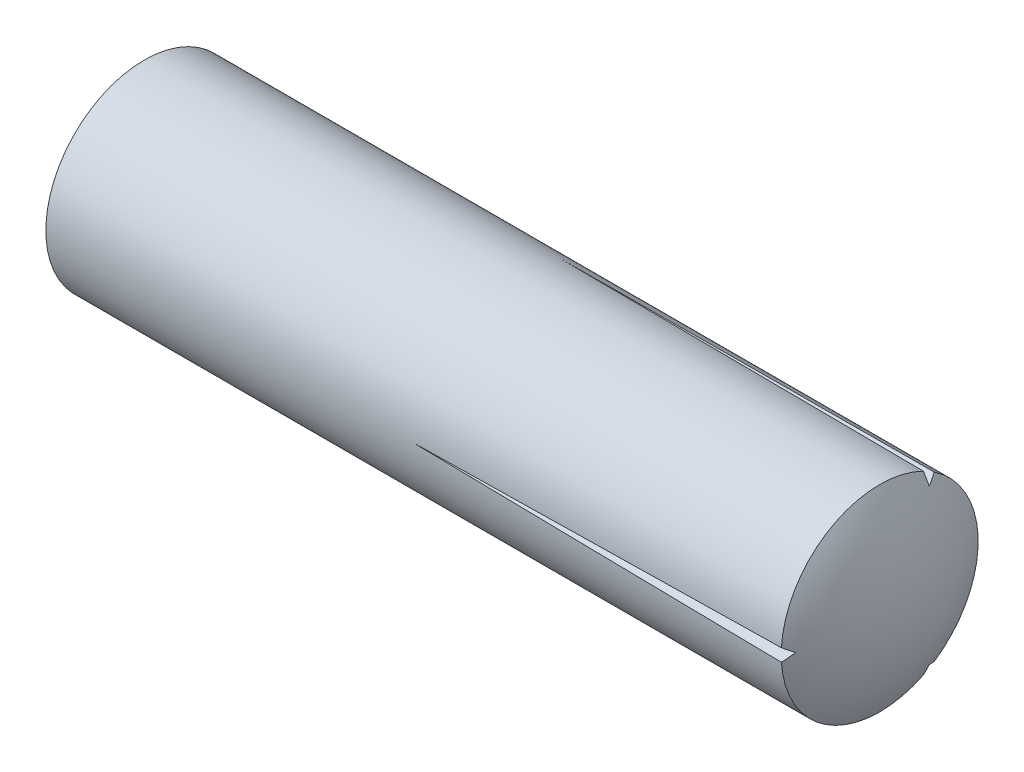
SolidWorks part; units mm, degrees
revolve "Base-Revolve" add sketch "Sketch1" angle 360 about L0
sketch "Sketch1" plane through (0, 0, 0) normal (0, 0, 1) x (1, 0, 0)
  line L0 (-40, 0) -> (40, 0) construction
  line L1 (-100, 0) -> (-100, 1.25)
  line L2 (-96.6819, 12.5) -> (-3.3494, 12.5)
  line L4 (0, 0) -> (-100, 0)
  arc A0 (-96.6819, 12.5) -> (-100, 1.25) centre (-75.0313, 0) ccw
  arc A1 (0, 0) -> (-3.3494, 12.5) centre (-25, 0) ccw
  dimension "D1" = 25
  dimension "D2" = 25
  dimension "Diameter" = 25
  dimension "Length" = 100
  dimension "D3" = 2.5
ref_plane "Plane1" through (0, 0, 0) normal (0, 0, 1) x (1, 0, 0)
ref_plane "Plane2" through (0, 0, 0) normal (0, 1, 0) x (1, 0, 0)
ref_plane "Plane3" through (0, 0, 0) normal (1, 0, 0) x (0, 0, -1)
sketch "Sketch2" plane through (0, 0, 0) normal (1, 0, 0) x (0, 0, -1)
  line L0 (0, 0) -> (-15, 0) construction
  line L1 (-11.25, 0) -> (-12.5, 0.8753)
  line L2 (-11.25, 0) -> (-12.5, -0.8753)
  line L3 (-12.5, -0.8753) -> (-12.5, 0.8753)
  circle A0 centre (0, 0) radius 11.25 construction
  circle A1 centre (0, 0) radius 12.5 construction
  dimension "D1" = 22.5
  dimension "D2" = 70
  dimension "D3" = 35
sketch "Sketch4" plane through (0, 0, 0) normal (0, 1, 0) x (1, 0, 0)
  line L0 (-110, 0) -> (10, 0) construction
  line L1 (-40, 0) -> (40, 0) construction
  line L2 (0, -11.25) -> (-50, -12.5)
  dimension "D1" = 22.5
  dimension "D2" = 50
  dimension "D3" = 25
sweep "Cut-Sweep1" cut profiles "Sketch2" path "Sketch4"
pattern_circular "CirPattern1" count 3 over 360 about axis through (0, 0, 0) along (1, 0, 0) of "Cut-Sweep1"
equation "\"D1@Sketch1\" = \"Diameter@Sketch1\""
equation "\"D2@Sketch1\" = \"Diameter@Sketch1\""
equation "\"D3@Sketch1\" = \"Diameter@Sketch1\" * .1"
equation "\"D1@Sketch2\" = \"Diameter@Sketch1\" * .9"
equation "\"D3@Sketch2\" = \"D2@Sketch2\" / 2"
equation "\"D1@Sketch4\" = \"D1@Sketch2\""
equation "\"D2@Sketch4\" = \"Length@Sketch1\" / 2"
equation "\"D3@Sketch4\" = \"Diameter@Sketch1\""
